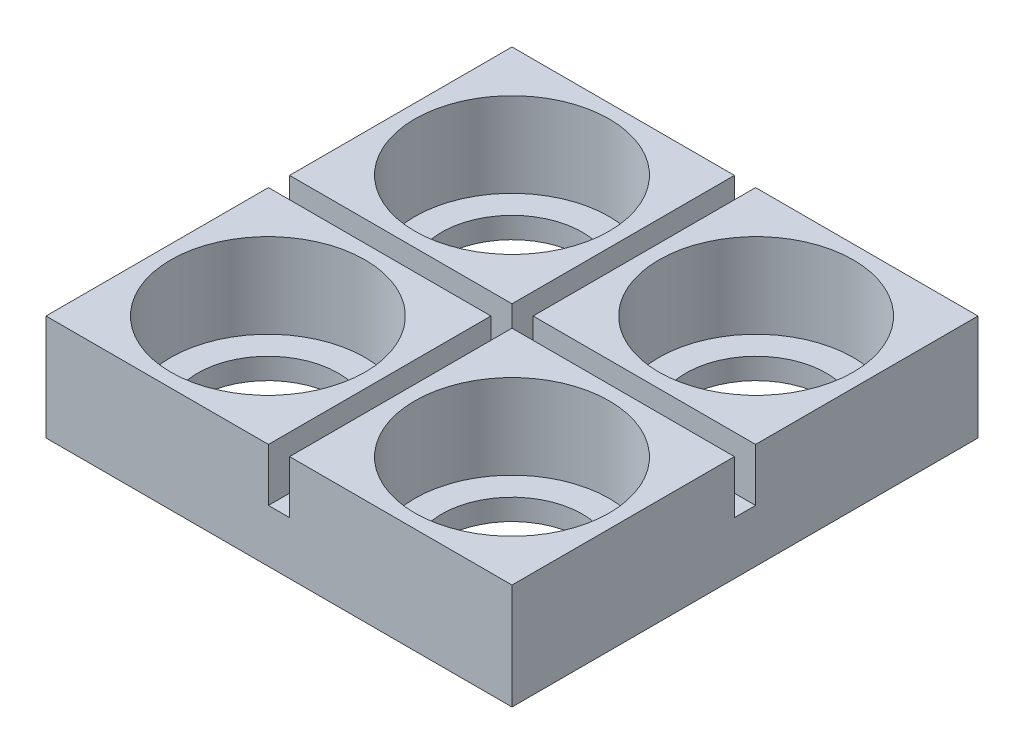
SolidWorks part; units mm, degrees
material "Melamine resin"
ref_plane "Front Plane" through (0, 0, 0) normal (0, 0, 1) x (1, 0, 0)
ref_plane "Top Plane" through (0, 0, 0) normal (0, 1, 0) x (1, 0, 0)
ref_plane "Right Plane" through (0, 0, 0) normal (1, 0, 0) x (0, 0, -1)
sketch "Sketch1" plane through (0, 0, 0) normal (0, 1, 0) x (1, 0, 0)
  line L1 (0, 22.05) -> (44.1, 22.05)
  line L2 (0, 22.05) -> (0, -22.05)
  line L3 (0, -22.05) -> (44.1, -22.05)
  line L4 (44.1, 22.05) -> (44.1, -22.05)
  point P4 (0, 0)
  dimension "D1" = 44.1
  dimension "D2" = 44.1
extrude "Boss-Extrude1" add sketch "Sketch1" along normal blind 10
sketch "Sketch2" plane through (0, 10, 0) normal (0, 1, 0) x (1, 0, 0)
  line L0 (44.1, 22.05) -> (0, 22.05) construction
  line L2 (22.05, 22.05) -> (22.05, -22.05) construction
  line L3 (0, -22.05) -> (44.1, -22.05) construction
  line L4 (22.05, 22.05) -> (0, 22.05)
  line L6 (0, 22.05) -> (0, -22.05) construction
  circle A0 centre (10.5, 11.55) radius 9.2
  dimension "D1" = 18.4
  dimension "D2" = 10.5
  dimension "D3" = 10.5
extrude "Cut-Extrude1" cut sketch "Sketch2" against normal blind 8 contours A0
sketch "Sketch5" plane through (0, 2, 0) normal (0, 1, 0) x (1, 0, 0)
  circle A0 centre (10.5, 11.55) radius 6.65
  dimension "D1" = 13.3
extrude "Cut-Extrude4" cut sketch "Sketch5" against normal through all
mirror "Mirror1" about plane through (0, 0, 0) normal (0, 0, 1) of "Cut-Extrude4", "Cut-Extrude1"
ref_plane "Plane2" through (22.05, 0, 0) normal (1, 0, 0) x (0, 0, -1)
mirror "Mirror2" about plane through (22.05, 0, 0) normal (1, 0, 0) of "Cut-Extrude1", "Mirror1", "Cut-Extrude4"
sketch "Sketch4" plane through (0, 10, 0) normal (0, 1, 0) x (1, 0, 0)
  line L0 (44.1, 22.05) -> (0, 22.05) construction
  line L1 (21.05, 22.05) -> (23.05, 22.05)
  line L2 (21.05, 22.05) -> (21.05, 1)
  line L3 (21.05, -23.3627) -> (23.05, -23.3627)
  line L4 (23.05, 22.05) -> (23.05, 1)
  line L5 (22.05, -5.5) -> (22.05, 5.5) construction
  line L6 (23.05, -1) -> (23.05, -23.3627)
  line L11 (0, 1) -> (21.05, 1)
  line L12 (0, 1) -> (0, -1)
  line L13 (0, -1) -> (21.05, -1)
  line L14 (46.2514, 1) -> (46.2514, -1)
  line L15 (21.05, -1) -> (21.05, -23.3627)
  line L16 (23.05, 1) -> (46.2514, 1)
  line L17 (23.05, -1) -> (46.2514, -1)
  point P6 (22.05, 22.05)
  point P13 (0, 0)
  dimension "D1" = 2
  dimension "D2" = 2
extrude "Cut-Extrude3" cut sketch "Sketch4" against normal blind 5
